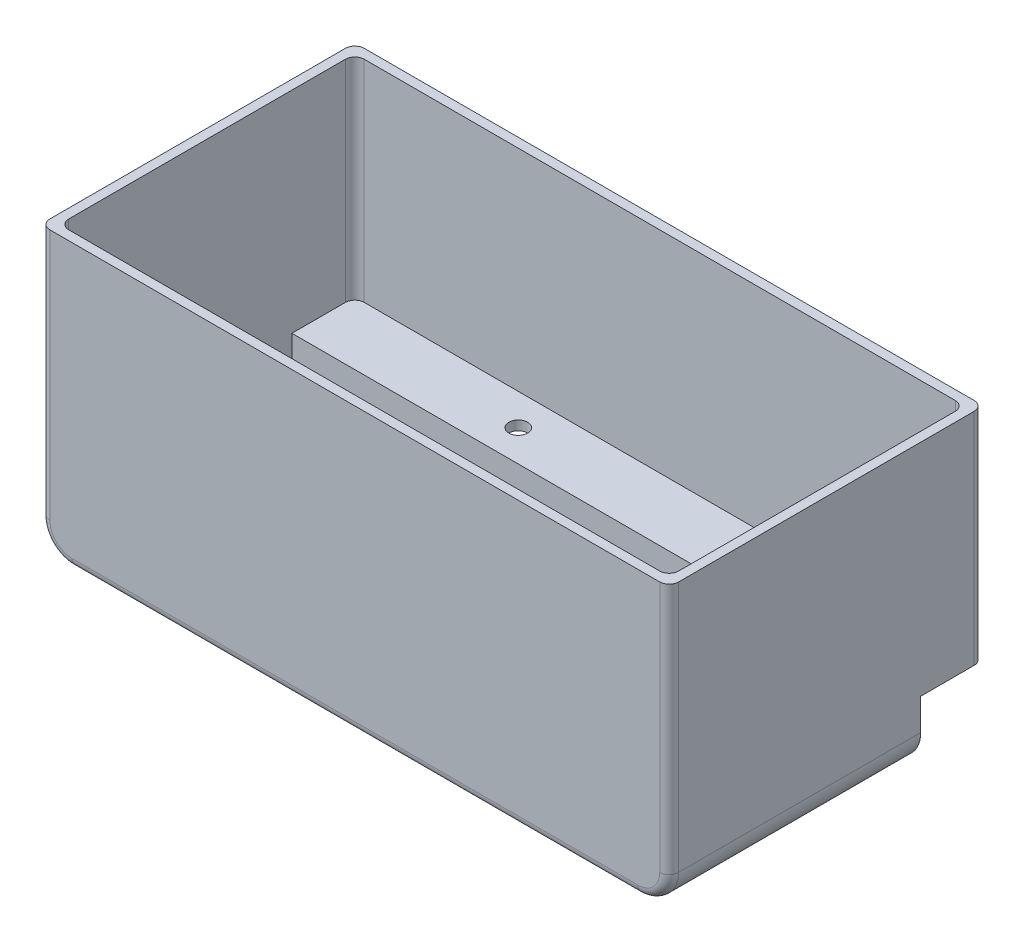
SolidWorks part; units mm, degrees
ref_plane "前基準面" through (0, 0, 0) normal (0, 0, 1) x (1, 0, 0)
ref_plane "上基準面" through (0, 0, 0) normal (0, 1, 0) x (1, 0, 0)
ref_plane "右基準面" through (0, 0, 0) normal (1, 0, 0) x (0, 0, -1)
sketch "草圖1" plane through (0, 0, 0) normal (0, 1, 0) x (1, 0, 0)
  line L1 (-100, -50) -> (100, -50)
  line L2 (-100, -50) -> (-100, 50)
  line L3 (-100, 50) -> (100, 50)
  line L4 (100, -50) -> (100, 50)
  line L5 (-100, -50) -> (100, 50) construction
  line L6 (-100, 50) -> (100, -50) construction
  point P0 (0, 0)
  dimension "D1" = 200
  dimension "D2" = 100
extrude "填料-伸長1" add sketch "草圖1" along normal blind 90
sketch "草圖2" plane through (100, 0, 0) normal (1, 0, 0) x (0, 0, -1)
  line L1 (50, 0) -> (30, 0)
  line L2 (50, 0) -> (50, 20)
  line L3 (50, 20) -> (30, 20)
  line L4 (30, 0) -> (30, 20)
  dimension "D1" = 20
  dimension "D2" = 20
extrude "除料-伸長1" cut sketch "草圖2" against normal up to vertex (200 mm away)
fillet "圓角1" radius 10 2 edges at (-100, 0, 10) (100, 0, 10)
shell "薄殼1" thickness 3
fillet "圓角2" radius 3 14 edges at (-100, 55, -50) (100, 55, -50) (-97.0711, 2.9289, 50) (0, 0, 50) (97.0711, 2.9289, 50) (-100, 50, 50) (100, 50, 50) (94.9497, 5.0503, 47) (0, 3, 47) (-94.9497, 5.0503, 47) (97, 56.5, -47) (97, 50, 47) (-97, 50, 47) (-97, 56.5, -47)
sketch "草圖3" plane through (0, 23, 0) normal (0, 1, 0) x (1, 0, 0)
  line L0 (94, 47) -> (-94, 47) construction
  circle A0 centre (-35, 37) radius 3
  circle A1 centre (35, 37) radius 3
  point P7 (0, 0)
  dimension "D1" = 6
  dimension "D2" = 6
  dimension "D3" = 10
  dimension "D4" = 70
  dimension "D5" = 35
extrude "除料-伸長2" cut sketch "草圖3" against normal blind 3
